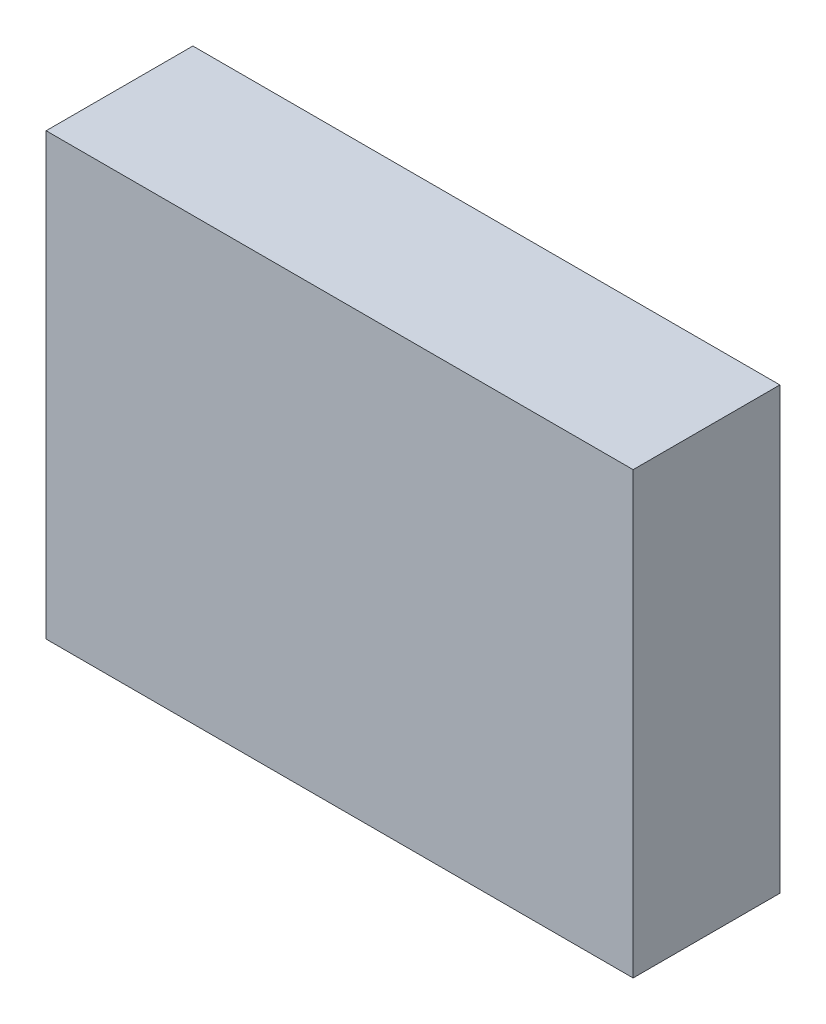
SolidWorks part; units mm, degrees
ref_plane "前视基准面" through (0, 0, 0) normal (0, 0, 1) x (1, 0, 0)
ref_plane "上视基准面" through (0, 0, 0) normal (0, 1, 0) x (1, 0, 0)
ref_plane "右视基准面" through (0, 0, 0) normal (1, 0, 0) x (0, 0, -1)
other "Configuration Table"
sketch "草图1" plane through (0, 0, 0) normal (0, 0, 1) x (1, 0, 0)
  line L1 (-40, -30) -> (40, -30)
  line L2 (-40, -30) -> (-40, 30)
  line L3 (-40, 30) -> (40, 30)
  line L4 (40, -30) -> (40, 30)
  line L5 (-40, -30) -> (40, 30) construction
  line L6 (-40, 30) -> (40, -30) construction
  point P0 (0, 0)
extrude "凸台-拉伸1" add sketch "草图1" along normal blind 20
